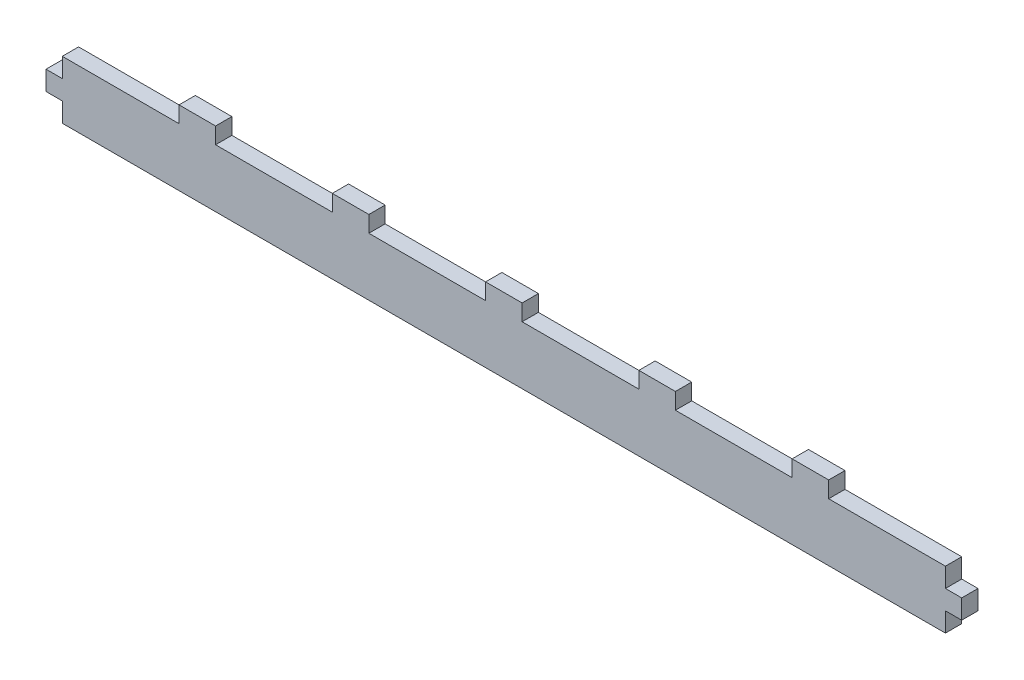
SolidWorks part; units mm, degrees
ref_plane "Front Plane" through (0, 0, 0) normal (0, 0, 1) x (1, 0, 0)
ref_plane "Top Plane" through (0, 0, 0) normal (0, 1, 0) x (1, 0, 0)
ref_plane "Right Plane" through (0, 0, 0) normal (1, 0, 0) x (0, 0, -1)
sketch "Model" plane through (0, 0, 0) normal (0, 0, 1) x (1, 0, 0)
  line L0 (145, 12.7) -> (145, 19.05)
  line L1 (-145, 0) -> (145, 0)
  line L2 (-145, 0) -> (-145, 6.35)
  line L3 (-145, 19.05) -> (-106.666, 19.05)
  line L4 (145, 0) -> (145, 6.35)
  line L5 (145, 6.35) -> (150.35, 6.35)
  line L6 (-145, 12.7) -> (-145, 19.05)
  line L7 (145, 12.7) -> (150.35, 12.7)
  line L8 (150.35, 6.35) -> (150.35, 12.7)
  line L9 (-145, 6.35) -> (-150.35, 6.35)
  line L10 (0, 0) -> (0, 43.2798) construction
  line L11 (-145, 12.7) -> (-150.35, 12.7)
  line L12 (-150.35, 6.35) -> (-150.35, 12.7)
  line L13 (6, 19.05) -> (44.333, 19.05)
  line L14 (6, 24.4) -> (-6, 24.4)
  line L15 (6, 24.4) -> (6, 19.05)
  line L16 (56.333, 24.4) -> (44.333, 24.4)
  line L17 (-6, 24.4) -> (-6, 19.05)
  line L18 (6, 24.4) -> (-6, 19.05) construction
  line L19 (6, 19.05) -> (-6, 24.4) construction
  line L20 (56.333, 24.4) -> (56.333, 19.05)
  line L21 (44.333, 24.4) -> (44.333, 19.05)
  line L22 (56.333, 24.4) -> (44.333, 19.05) construction
  line L23 (56.333, 19.05) -> (44.333, 24.4) construction
  line L24 (106.666, 24.4) -> (94.666, 24.4)
  line L25 (106.666, 24.4) -> (106.666, 19.05)
  line L26 (94.666, 24.4) -> (94.666, 19.05)
  line L27 (106.666, 24.4) -> (94.666, 19.05) construction
  line L28 (106.666, 19.05) -> (94.666, 24.4) construction
  line L29 (56.333, 19.05) -> (94.666, 19.05)
  line L30 (106.666, 19.05) -> (145, 19.05)
  line L31 (-44.333, 24.4) -> (-56.333, 24.4)
  line L32 (-44.333, 24.4) -> (-44.333, 19.05)
  line L33 (-56.333, 24.4) -> (-56.333, 19.05)
  line L34 (-44.333, 24.4) -> (-56.333, 19.05) construction
  line L35 (-44.333, 19.05) -> (-56.333, 24.4) construction
  line L36 (-94.666, 24.4) -> (-106.666, 24.4)
  line L37 (-94.666, 24.4) -> (-94.666, 19.05)
  line L38 (-106.666, 24.4) -> (-106.666, 19.05)
  line L39 (-94.666, 24.4) -> (-106.666, 19.05) construction
  line L40 (-94.666, 19.05) -> (-106.666, 24.4) construction
  line L41 (-44.333, 19.05) -> (-6, 19.05)
  line L42 (-94.666, 19.05) -> (-56.333, 19.05)
  point P14 (0, 21.725)
  point P20 (50.333, 21.725)
  point P25 (100.666, 21.725)
  point P30 (-50.333, 21.725)
  point P35 (-100.666, 21.725)
  dimension "D2" = 5.35
  dimension "D4" = 6.35
  dimension "D6" = 19.05
  dimension "D8" = 290
  dimension "D10" = 12
  dimension "D12" = 5.35
  dimension "D15" = 38.333
  dimension "D17" = 38.333
  dimension "D13" = 3
  dimension "D16" = 3
extrude "Boss-Extrude1" add sketch "Model" along normal blind 5.35
equation "\"mdfthick\"=5.35"
equation "\"D2@Model\"=\"mdfthick\""
equation "\"D12@Model\"=\"mdfthick\""
equation "\"D1@Boss-Extrude1\"=\"mdfthick\""
